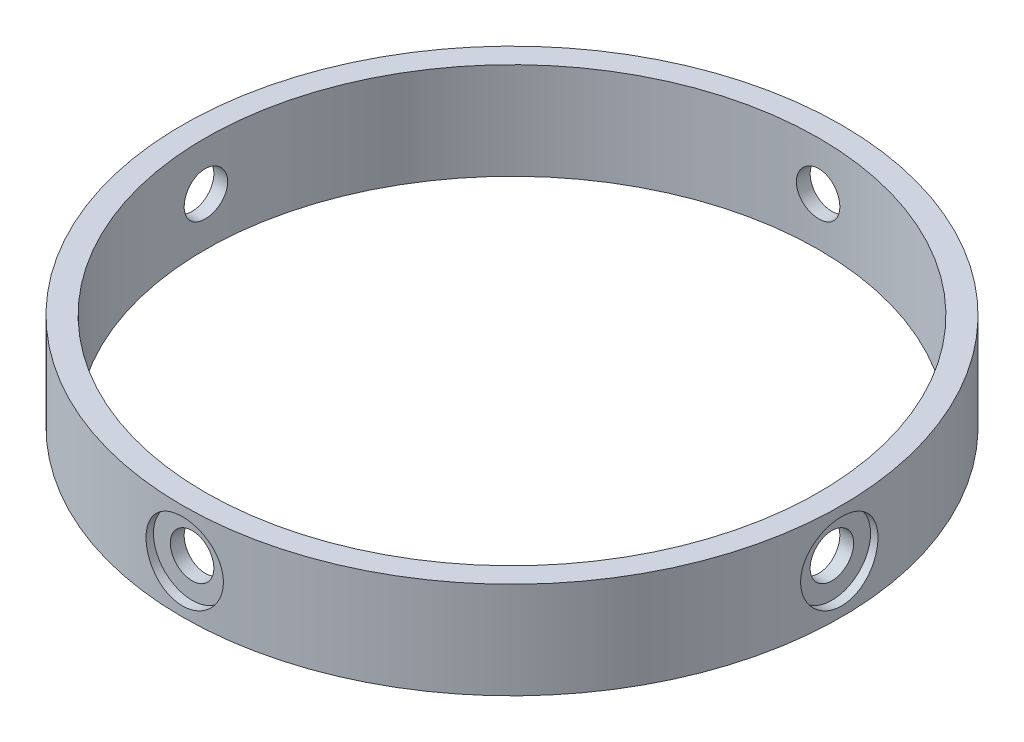
SolidWorks part; units mm, degrees
ref_plane "Front Plane" through (0, 0, 0) normal (0, 0, 1) x (1, 0, 0)
ref_plane "Top Plane" through (0, 0, 0) normal (0, 1, 0) x (1, 0, 0)
ref_plane "Right Plane" through (0, 0, 0) normal (1, 0, 0) x (0, 0, -1)
sketch "Sketch1" plane through (0, 0, 0) normal (0, 1, 0) x (1, 0, 0)
  circle A0 centre (0, 0) radius 31.75
  circle A1 centre (0, 0) radius 34.1
  dimension "D1" = 63.5
  dimension "D2" = 68.2
extrude "Boss-Extrude1" add sketch "Sketch1" along normal mid plane 10
ref_plane "Plane1" through (0, 0, -34.1) normal (0, 0, -1) x (-1, 0, 0)
sketch "Sketch2" plane through (0, 0, -34.1) normal (0, 0, -1) x (-1, 0, 0)
  circle A0 centre (0, 0) radius 4
  dimension "D1" = 8
extrude "Cut-Extrude1" cut sketch "Sketch2" against normal blind 1
sketch "Sketch3" plane through (0, 0, -33.1) normal (0, 0, -1) x (-1, 0, 0)
  circle A0 centre (0, 0) radius 2.25
  dimension "D1" = 4.5
extrude "Cut-Extrude2" cut sketch "Sketch3" against normal up to surface (1.4298 mm away)
pattern_circular "CirPattern1" count 4 every 90 about axis through (0, 0, 0) along (0, 1, 0) of "Cut-Extrude1", "Cut-Extrude2"
